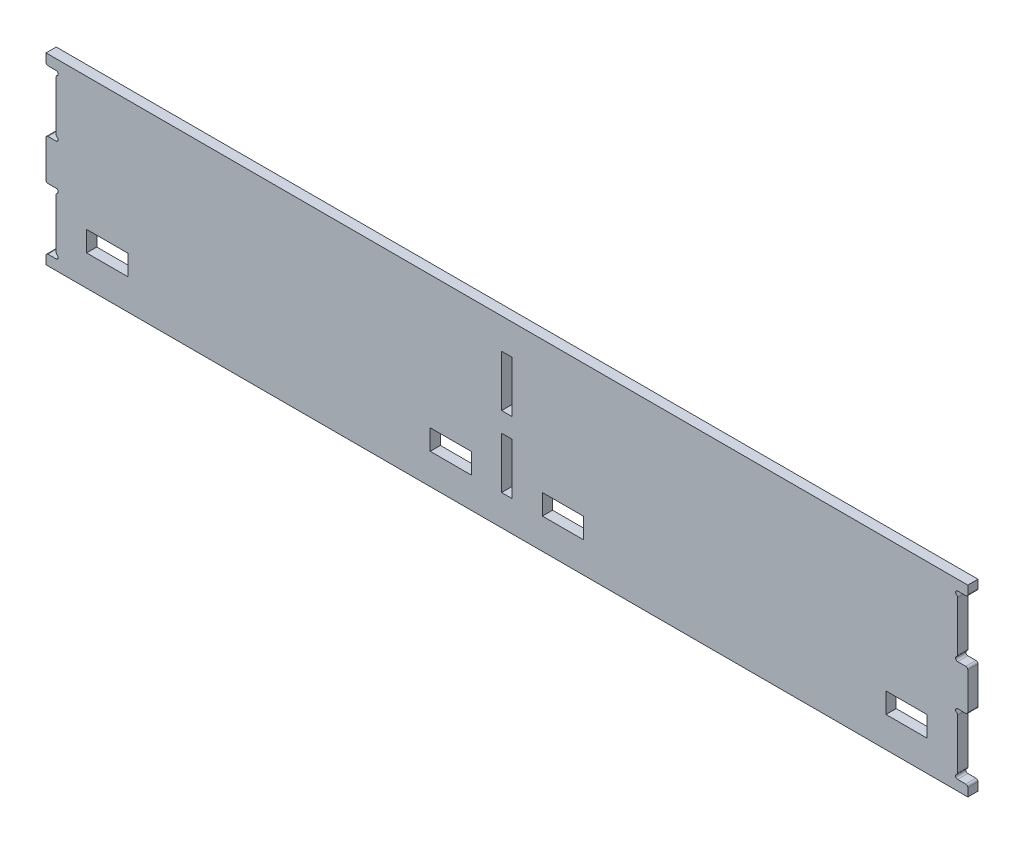
SolidWorks part; units mm, degrees
ref_plane "Front Plane" through (0, 0, 0) normal (0, 0, 1) x (1, 0, 0)
ref_plane "Top Plane" through (0, 0, 0) normal (0, 1, 0) x (1, 0, 0)
ref_plane "Right Plane" through (0, 0, 0) normal (1, 0, 0) x (0, 0, -1)
sketch "Sketch1" plane through (0, 0, 0) normal (0, 0, 1) x (1, 0, 0)
  line L1 (-226, -45) -> (226, -45)
  line L2 (-226, -45) -> (-226, 45)
  line L3 (-226, 45) -> (226, 45)
  line L4 (226, -45) -> (226, 45)
  line L5 (-226, -45) -> (226, 45) construction
  line L6 (-226, 45) -> (226, -45) construction
  point P0 (0, 0)
  dimension "D1" = 90
  dimension "D2" = 452
extrude "Boss-Extrude1" add sketch "Sketch1" along normal blind 5
sketch "Sketch2" plane through (0, 0, 5) normal (0, 0, 1) x (1, 0, 0)
  line L0 (226, 45) -> (-226, 45) construction
  line L1 (-2.6, 30) -> (2.6, 30)
  line L2 (-2.6, 30) -> (-2.6, 4.8)
  line L3 (-2.6, 4.8) -> (2.6, 4.8)
  line L4 (2.6, 30) -> (2.6, 4.8)
  line L5 (-2.6, -4.8) -> (2.6, -4.8)
  line L6 (-2.6, -4.8) -> (-2.6, -30)
  line L7 (-2.6, -30) -> (2.6, -30)
  line L8 (2.6, -4.8) -> (2.6, -30)
  line L9 (-226, -45) -> (226, -45) construction
  line L10 (0, -2.75) -> (0, 2.75) construction
  point P10 (0, -30)
  point P15 (0, -4.8)
  dimension "D1" = 15
  dimension "D2" = 25.2
  dimension "D3" = 25.2
  dimension "D4" = 15
  dimension "D5" = 0
  dimension "D6" = 5.2
extrude "Cut-Extrude1" cut sketch "Sketch2" against normal through all
sketch "Sketch3" plane through (0, 0, 5) normal (0, 0, 1) x (1, 0, 0)
  circle A8 centre (-77.6, 29) radius 1
  circle A9 centre (-72.4, 29) radius 1
  circle A10 centre (-77.6, 5.8) radius 1
  circle A11 centre (-72.4, 5.8) radius 1
  circle A24 centre (222.4, 29) radius 1
  circle A25 centre (227.6, 29) radius 1
  circle A26 centre (222.4, 5.8) radius 1
  circle A27 centre (227.6, 5.8) radius 1
  circle A28 centre (222.4, -5.8) radius 1
  circle A29 centre (227.6, -5.8) radius 1
  circle A30 centre (222.4, -29) radius 1
  circle A31 centre (227.6, -29) radius 1
sketch "Sketch4" plane through (-226, 0, 0) normal (-1, 0, 0) x (0, 0, 1)
  line L0 (0, 45) -> (0, -45) construction
  line L1 (0, 40) -> (5, 40)
  line L2 (0, 40) -> (0, 10)
  line L3 (0, 10) -> (5, 10)
  line L4 (5, 40) -> (5, 10)
  line L5 (5, 45) -> (5, -45) construction
  line L6 (5, -45) -> (0, -45) construction
  line L7 (0, -10) -> (5, -10)
  line L8 (0, -10) -> (0, -40)
  line L9 (0, -40) -> (5, -40)
  line L10 (5, -10) -> (5, -40)
  line L11 (5, 45) -> (0, 45) construction
  dimension "D1" = 5
  dimension "D2" = 30
  dimension "D3" = 30
  dimension "D4" = 5
extrude "Cut-Extrude5" cut sketch "Sketch4" against normal blind 5
mirror "Mirror2" about plane through (0, 0, 0) normal (1, 0, 0) of "Cut-Extrude5"
sketch "Sketch7" plane through (0, 0, 5) normal (0, 0, 1) x (1, 0, 0)
  line L0 (-221, 10) -> (-221, 40) construction
  line L1 (-221, -40) -> (-221, -10) construction
  line L2 (0, -2.75) -> (0, 2.75) construction
  circle A0 centre (-221, 39) radius 1
  circle A1 centre (-221, 11) radius 1
  circle A2 centre (-221, -11) radius 1
  circle A3 centre (-221, -39) radius 1
  circle A4 centre (221, -39) radius 1
  circle A5 centre (221, -11) radius 1
  circle A6 centre (221, 11) radius 1
  circle A7 centre (221, 39) radius 1
  dimension "D1" = 2
extrude "Cut-Extrude6" cut sketch "Sketch7" against normal through all
fillet "Fillet4" radius 1 16 edges at (-226, -40, 2.5) (-221, -38, 2.5) (-221, -12, 2.5) (-226, -10, 2.5) (-226, 10, 2.5) (-221, 12, 2.5) (-221, 38, 2.5) (-226, 40, 2.5) (226, -40, 2.5) (221, -38, 2.5) (221, -12, 2.5) (226, -10, 2.5) (226, 10, 2.5) (221, 12, 2.5) (221, 38, 2.5) (226, 40, 2.5)
extrude "Cut-Extrude7" cut sketch "Sketch8" against normal blind 10
sketch "Sketch8" plane through (0, -610.4562, 0) normal (0, 0, -1) x (-1, 0, 0)
  line L4 (-206.1, 590.4562) -> (-185.9, 590.4562)
  line L5 (-185.9, 590.4562) -> (-185.9, 580.4562)
  line L6 (-206.1, 580.4562) -> (-185.9, 580.4562)
  line L7 (-206.1, 590.4562) -> (-206.1, 580.4562)
  line L40 (-221, 570.4562) -> (-225, 570.4562)
  line L41 (-226, 569.4562) -> (-226, 565.4562)
  line L42 (-226, 565.4562) -> (226, 565.4562)
  line L43 (226, 565.4562) -> (226, 569.4562)
  line L44 (225, 570.4562) -> (221, 570.4562)
  line L45 (221, 573.1882) -> (221, 597.7241)
  line L46 (221, 600.4562) -> (225, 600.4562)
  line L47 (226, 601.4562) -> (226, 619.4562)
  line L48 (225, 620.4562) -> (221, 620.4562)
  line L49 (221, 623.1882) -> (221, 647.7241)
  line L50 (221, 650.4562) -> (225, 650.4562)
  line L51 (226, 651.4562) -> (226, 655.4562)
  line L52 (226, 655.4562) -> (-226, 655.4562)
  line L53 (-226, 655.4562) -> (-226, 651.4562)
  line L54 (-225, 650.4562) -> (-221, 650.4562)
  line L55 (-221, 647.7241) -> (-221, 623.1882)
  line L56 (-221, 620.4562) -> (-225, 620.4562)
  line L57 (-226, 619.4562) -> (-226, 601.4562)
  line L58 (-225, 600.4562) -> (-221, 600.4562)
  line L59 (-221, 597.7241) -> (-221, 573.1882)
  arc A48 (-225, 570.4562) -> (-226, 569.4562) centre (-225, 569.4562) ccw
  arc A49 (226, 569.4562) -> (225, 570.4562) centre (225, 569.4562) ccw
  arc A50 (220.5, 572.3222) -> (221, 570.4562) centre (221, 571.4562) ccw
  arc A51 (220.5, 572.3222) -> (221, 573.1882) centre (220, 573.1882) ccw
  arc A52 (221, 597.7241) -> (220.5, 598.5901) centre (220, 597.7241) ccw
  arc A53 (221, 600.4562) -> (220.5, 598.5901) centre (221, 599.4562) ccw
  arc A54 (225, 600.4562) -> (226, 601.4562) centre (225, 601.4562) ccw
  arc A55 (226, 619.4562) -> (225, 620.4562) centre (225, 619.4562) ccw
  arc A56 (220.5, 622.3222) -> (221, 620.4562) centre (221, 621.4562) ccw
  arc A57 (220.5, 622.3222) -> (221, 623.1882) centre (220, 623.1882) ccw
  arc A58 (221, 647.7241) -> (220.5, 648.5901) centre (220, 647.7241) ccw
  arc A59 (221, 650.4562) -> (220.5, 648.5901) centre (221, 649.4562) ccw
  arc A60 (225, 650.4562) -> (226, 651.4562) centre (225, 651.4562) ccw
  arc A61 (-226, 651.4562) -> (-225, 650.4562) centre (-225, 651.4562) ccw
  arc A62 (-220.5, 648.5901) -> (-221, 650.4562) centre (-221, 649.4562) ccw
  arc A63 (-220.5, 648.5901) -> (-221, 647.7241) centre (-220, 647.7241) ccw
  arc A64 (-221, 623.1882) -> (-220.5, 622.3222) centre (-220, 623.1882) ccw
  arc A65 (-221, 620.4562) -> (-220.5, 622.3222) centre (-221, 621.4562) ccw
  arc A66 (-225, 620.4562) -> (-226, 619.4562) centre (-225, 619.4562) ccw
  arc A67 (-226, 601.4562) -> (-225, 600.4562) centre (-225, 601.4562) ccw
  arc A68 (-220.5, 598.5901) -> (-221, 600.4562) centre (-221, 599.4562) ccw
  arc A69 (-220.5, 598.5901) -> (-221, 597.7241) centre (-220, 597.7241) ccw
  arc A70 (-221, 573.1882) -> (-220.5, 572.3222) centre (-220, 573.1882) ccw
  arc A71 (-221, 570.4562) -> (-220.5, 572.3222) centre (-221, 571.4562) ccw
mirror "Mirror3" about plane through (0, 0, 0) normal (1, 0, 0) of "Cut-Extrude7"
extrude "Cut-Extrude8" cut sketch "Sketch9" against normal blind 300
sketch "Sketch9" plane through (0, -610.4562, -223.6) normal (0, 0, -1) x (-1, 0, 0)
  line L4 (17.4, 590.4562) -> (37.6, 590.4562)
  line L5 (37.6, 590.4562) -> (37.6, 580.4562)
  line L6 (17.4, 580.4562) -> (37.6, 580.4562)
  line L7 (17.4, 590.4562) -> (17.4, 580.4562)
mirror "Mirror4" about plane through (0, 0, 0) normal (1, 0, 0) of "Cut-Extrude8"
